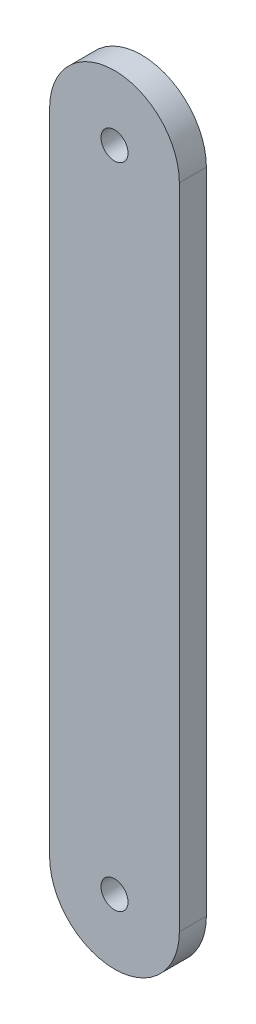
SolidWorks part; units mm, degrees
ref_plane "前视基准面" through (0, 0, 0) normal (0, 0, 1) x (1, 0, 0)
ref_plane "上视基准面" through (0, 0, 0) normal (0, 1, 0) x (1, 0, 0)
ref_plane "右视基准面" through (0, 0, 0) normal (1, 0, 0) x (0, 0, -1)
ref_plane "基准面4" through (0, 0, 5) normal (0, 0, 1) x (1, 0, 0)
sketch "草图1" plane through (0, 0, 5) normal (0, 0, 1) x (1, 0, 0)
  line L0 (12, -60) -> (12, 60)
  line L1 (-12, 60) -> (-12, -60)
  circle A0 centre (0, -60) radius 2.5
  circle A1 centre (0, 60) radius 2.5
  arc A2 (12, 60) -> (-12, 60) centre (0, 60) ccw
  arc A3 (-12, -60) -> (12, -60) centre (0, -60) ccw
  dimension "D1" = 5
  dimension "D2" = 5
extrude "凸台-拉伸1" add sketch "草图1" against normal blind 5
